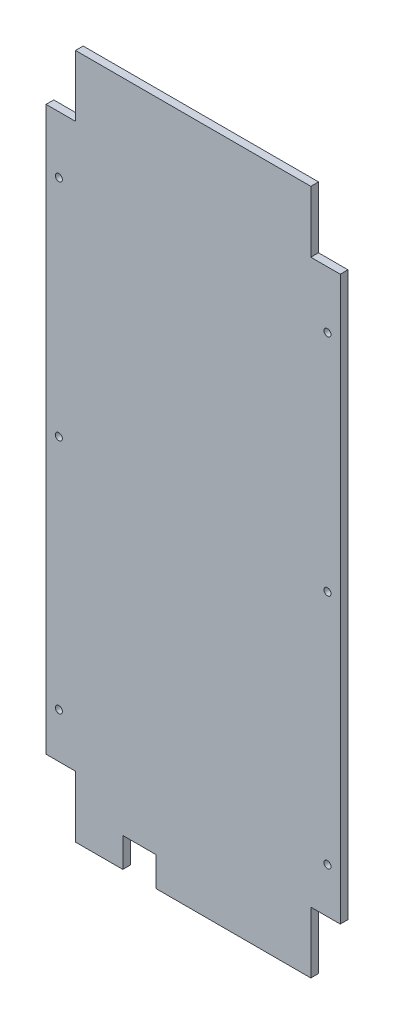
SolidWorks part; units mm, degrees
ref_plane "Front Plane" through (0, 0, 0) normal (0, 0, 1) x (1, 0, 0)
ref_plane "Top Plane" through (0, 0, 0) normal (0, 1, 0) x (1, 0, 0)
ref_plane "Right Plane" through (0, 0, 0) normal (1, 0, 0) x (0, 0, -1)
sketch "Sketch1" plane through (0, 0, 0) normal (0, 0, 1) x (1, 0, 0)
  line L0 (95.8148, -438.5873) -> (95.8148, -390.5873)
  line L2 (-111.1852, 49.4127) -> (-111.1852, -390.5873)
  line L4 (118.8148, 49.4127) -> (118.8148, -390.5873)
  line L5 (95.8148, -390.5873) -> (118.8148, -390.5873)
  line L6 (-88.1852, -438.5873) -> (-88.1852, -390.5873)
  line L7 (-88.1852, -390.5873) -> (-111.1852, -390.5873)
  line L8 (-111.1852, 49.4127) -> (-88.1852, 49.4127)
  line L9 (-88.1852, 49.4127) -> (-88.1852, 97.4127)
  line L10 (95.8148, 97.4127) -> (95.8148, 49.4127)
  line L11 (95.8148, 49.4127) -> (118.8148, 49.4127)
  line L12 (-51.1852, -415.5873) -> (-25.1852, -415.5873)
  line L13 (-51.1852, -415.5873) -> (-51.1852, -438.5873)
  line L15 (-88.1852, 97.4127) -> (95.8148, 97.4127)
  line L16 (-25.1852, -415.5873) -> (-25.1852, -438.5873)
  line L17 (95.8148, -438.5873) -> (-25.1852, -438.5873)
  line L19 (-88.1852, -438.5873) -> (-51.1852, -438.5873)
  dimension "D1" = 230
  dimension "D2" = 48
  dimension "D3" = 23
  dimension "D4" = 23
  dimension "D5" = 26
  dimension "D6" = 536
  dimension "D7" = 144
  dimension "D8" = 48
extrude "Boss-Extrude1" add sketch "Sketch1" along normal blind 6
sketch "Sketch2" plane through (0, 0, 0) normal (0, 0, -1) x (-1, 0, 0)
  line L0 (-118.8148, -390.5873) -> (-118.8148, 49.4127) construction
  line L1 (111.1852, 49.4127) -> (111.1852, -390.5873) construction
  circle A0 centre (-108.8148, -170.5873) radius 2.75
  circle A1 centre (-108.8148, 4.8349) radius 2.75
  circle A2 centre (-108.8148, -355.3367) radius 2.75
  circle A3 centre (101.1852, 4.8349) radius 2.75
  circle A4 centre (101.1852, -170.5873) radius 2.75
  circle A5 centre (101.1852, -355.3367) radius 2.75
  dimension "D1" = 5.5
  dimension "D2" = 10
  dimension "D3" = 10
extrude "Cut-Extrude1" cut sketch "Sketch2" against normal blind 10
